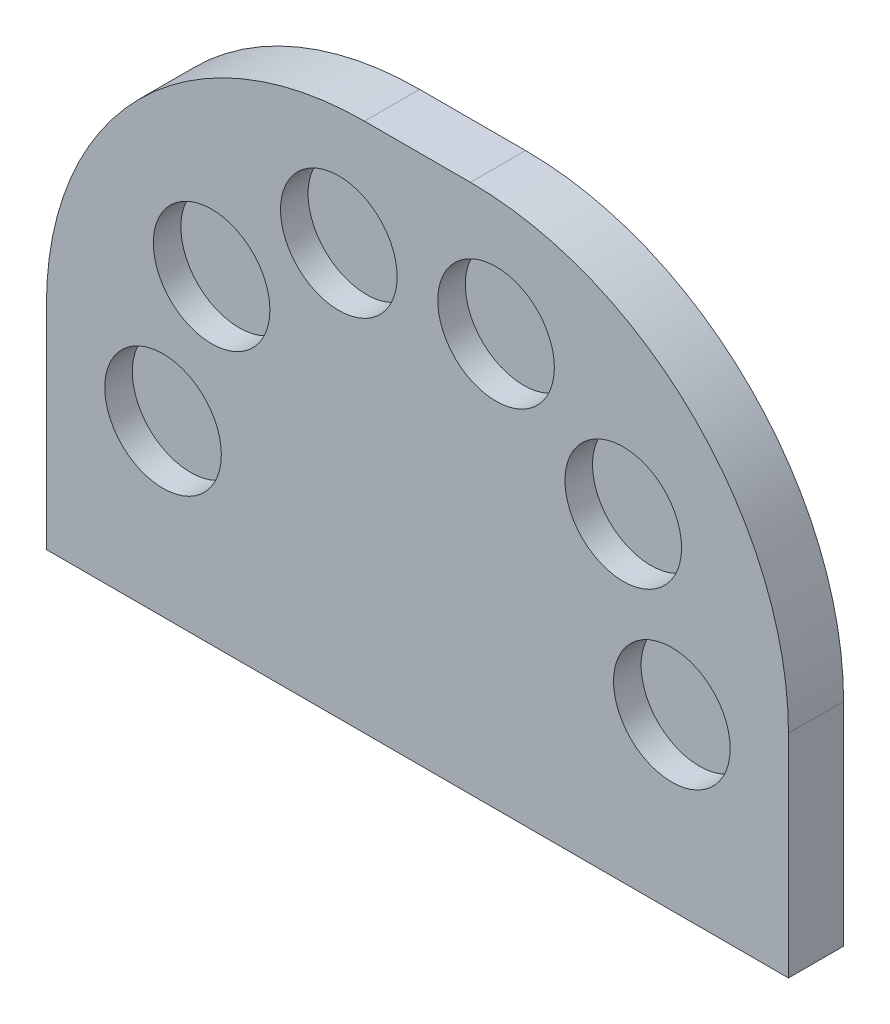
SolidWorks part; units mm, degrees
ref_plane "Front Plane" through (0, 0, 0) normal (0, 0, 1) x (1, 0, 0)
ref_plane "Top Plane" through (0, 0, 0) normal (0, 1, 0) x (1, 0, 0)
ref_plane "Right Plane" through (0, 0, 0) normal (1, 0, 0) x (0, 0, -1)
ref_plane "Plane1" through (0, 0, 26) normal (0, 0, 1) x (1, 0, 0)
sketch "Sketch1" plane through (0, 0, 26) normal (0, 0, 1) x (1, 0, 0)
  line L0 (350, 0) -> (350, 250)
  line L1 (350, 250) -> (0, 250)
  line L2 (0, 250) -> (0, 0)
  line L3 (0, 0) -> (350, 0)
extrude "Boss-Extrude1" add sketch "Sketch1" against normal blind 26
sketch "Sketch2" plane through (0, 0, 0) normal (0, 0, -1) x (-1, 0, 0)
  line L0 (-280, 10) -> (-280, 50)
  line L1 (-280, 50) -> (-279, 50)
  line L2 (-279, 50) -> (-279, 10)
  line L3 (-279, 10) -> (-280, 10)
extrude "Boss-Extrude2" add sketch "Sketch2" along normal blind 50
hole_wizard "M48 Clearance Hole1" positions "Sketch4" profile "Sketch3" hole size "M48" standard "ANSI Metric"
sketch "Sketch4" plane through (0, 0, 26) normal (0, 0, 1) x (1, 0, 0)
  point P0 (55, 80)
  point P1 (212.082, 194.1268)
  point P2 (272.082, 150.5342)
  point P3 (295, 80)
  point P4 (137.918, 194.1268)
  point P5 (77.918, 150.5342)
sketch "Sketch3" plane through (55, 80, 26) normal (1, 0, 0) x (0, -1, 0)
  line L0 (0, 0) -> (0, 13)
  line L1 (0, 13) -> (27.5, 13)
  line L2 (27.5, 13) -> (27.5, 0)
  line L5 (27.5, 0) -> (0, 0)
  line L10 (0, 13) -> (-27.5, 13) construction
  line L11 (0, -6.35) -> (0, 107.95) construction
  dimension "Hole Dia." = 55
  dimension "Hole Depth" = 13
  dimension "Drill Angle" = 180
fillet "Fillet1" radius 150 2 edges at (0, 250, 13) (350, 250, 13)
